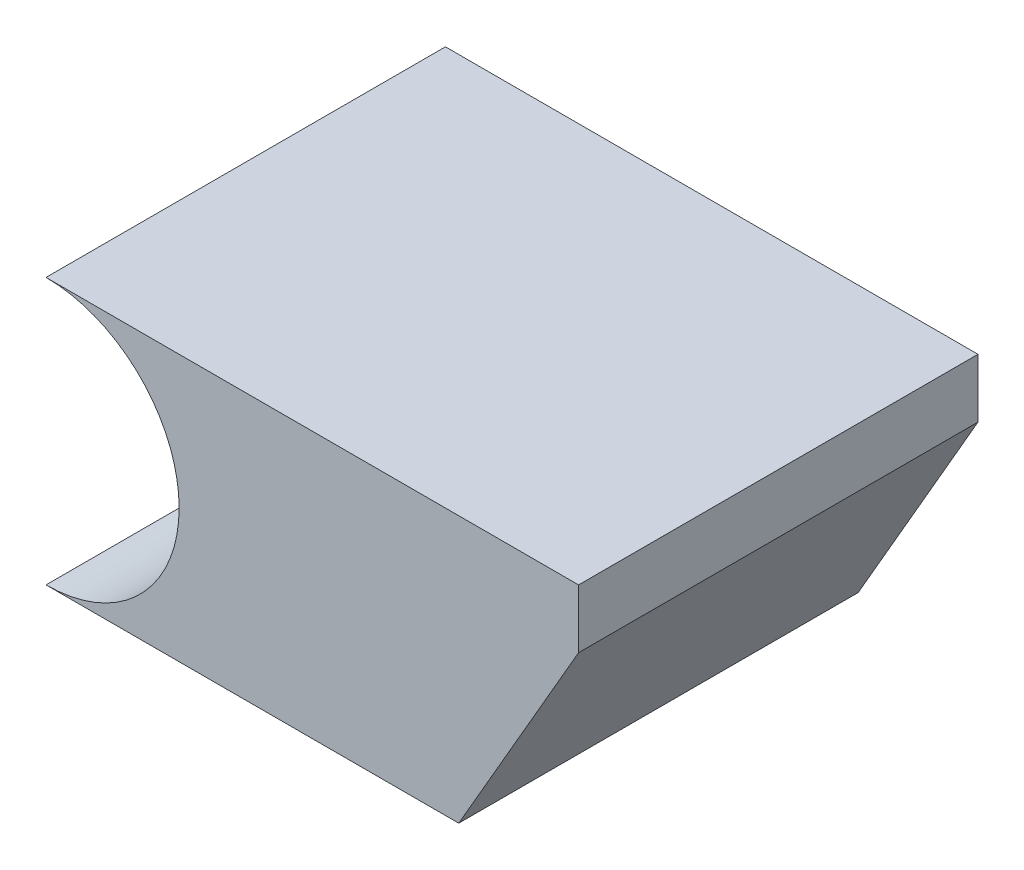
SolidWorks part; units mm, degrees
ref_plane "Front Plane" through (0, 0, 0) normal (0, 0, 1) x (1, 0, 0)
ref_plane "Top Plane" through (0, 0, 0) normal (0, 1, 0) x (1, 0, 0)
ref_plane "Right Plane" through (0, 0, 0) normal (1, 0, 0) x (0, 0, -1)
sketch "Sketch1" plane through (0, 0, 0) normal (0, 0, 1) x (1, 0, 0)
  line L1 (0, 0) -> (50.8, 0)
  line L3 (0, 25.4) -> (50.8, 25.4)
  line L4 (50.8, 0) -> (50.8, 25.4)
  arc A1 (0, 0) -> (0, 25.4) centre (0, 12.7) ccw
  point P5 (0, 0)
  dimension "D2" = 25.4
  dimension "D1" = 50.8
extrude "Boss-Extrude1" add sketch "Sketch1" along normal blind 38.1
chamfer "Chamfer1" distance 11.43 angle 60 1 edges at (50.8, 0, 19.05)
